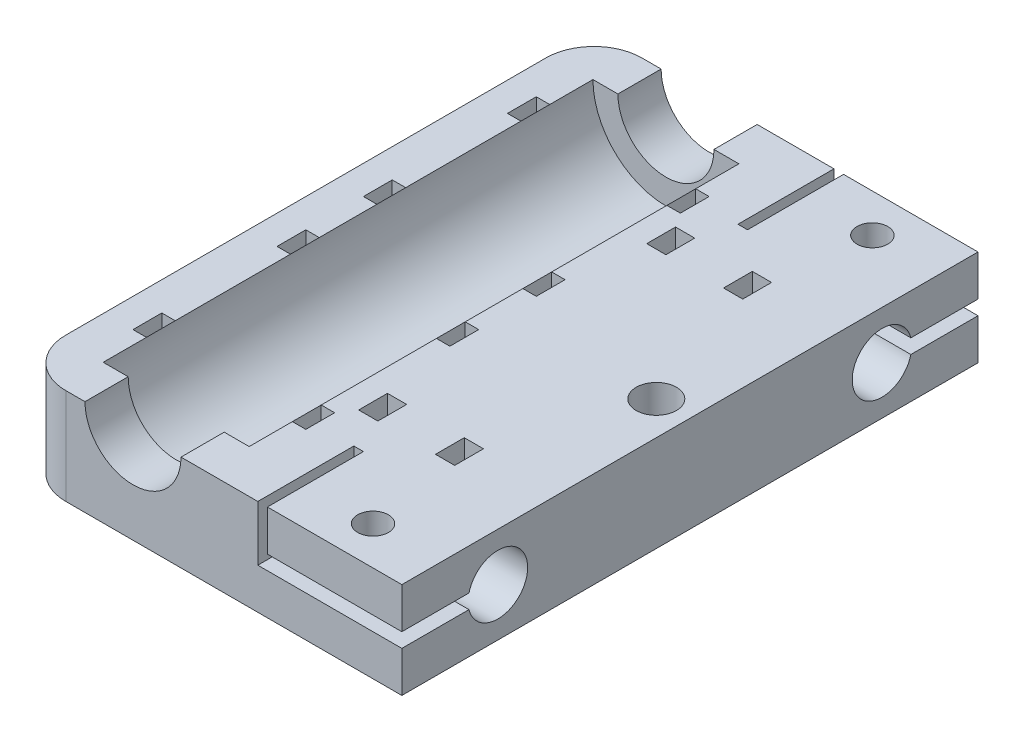
SolidWorks part; units mm, degrees
ref_plane "前基準面" through (0, 0, 0) normal (0, 0, 1) x (1, 0, 0)
ref_plane "上基準面" through (0, 0, 0) normal (0, 1, 0) x (1, 0, 0)
ref_plane "右基準面" through (0, 0, 0) normal (1, 0, 0) x (0, 0, -1)
sketch "草圖2" plane through (0, 0, 0) normal (0, 1, 0) x (1, 0, 0)
  line L1 (-20000, 30000) -> (20000, 30000)
  line L2 (-20000, 30000) -> (-20000, -30000)
  line L3 (-20000, -30000) -> (20000, -30000)
  line L4 (20000, 30000) -> (20000, -30000)
  line L5 (-20000, 30000) -> (20000, -30000) construction
  line L6 (-20000, -30000) -> (20000, 30000) construction
  point P0 (0, 0)
  dimension "D1" = 40000
  dimension "D2" = 60000
extrude "填料-伸長1" add sketch "草圖2" along normal blind 10000
sketch "草圖4" plane through (0, 0, 0) normal (0, 0, 1) x (1, 0, 0)
  line L0 (-20000, 10000) -> (20000, 10000) construction
  line L1 (-20000, 10000) -> (-20000, 0) construction
  circle A0 centre (-8000, 10000) radius 7600
  dimension "D1" = 15200
  dimension "D2" = 12000
extrude "除料-伸長2" cut sketch "草圖4" against normal mid plane 51000
sketch "草圖5" plane through (0, 0, 0) normal (0, 0, 1) x (1, 0, 0)
  circle A0 centre (-8000, 10000) radius 5000
  dimension "D1" = 10000
extrude "除料-伸長3" cut sketch "草圖5" against normal mid plane 80000
sketch "草圖6" plane through (0, 10000, 0) normal (0, 1, 0) x (1, 0, 0)
  line L0 (7000, 30000) -> (7000, -30000) construction
  line L1 (20000, 30000) -> (-3000, 30000) construction
  line L2 (-3000, -30000) -> (20000, -30000) construction
  line L3 (-13000, 25500) -> (-3000, 25500) construction
  line L4 (-20000, 0) -> (38738.6802, 0) construction
  line L5 (4000, 16500) -> (10000, 16500) construction
  line L6 (4000, 16500) -> (4000, 13500) construction
  line L7 (4000, 13500) -> (10000, 13500) construction
  line L8 (10000, 16500) -> (10000, 13500) construction
  line L9 (4000, 16500) -> (10000, 13500) construction
  line L10 (4000, 13500) -> (10000, 16500) construction
  line L11 (-20000, 30000) -> (-20000, -30000) construction
  line L12 (12000, -16500) -> (12000, -13500)
  line L13 (4000, 16500) -> (2000, 16500)
  line L14 (4000, 16500) -> (4000, 13500)
  line L15 (4000, 13500) -> (2000, 13500)
  line L16 (2000, 16500) -> (2000, 13500)
  line L17 (10000, 16500) -> (12000, 16500)
  line L18 (10000, 16500) -> (10000, 13500)
  line L19 (10000, 13500) -> (12000, 13500)
  line L20 (12000, 16500) -> (12000, 13500)
  line L21 (10000, -16500) -> (12000, -16500)
  line L22 (10000, -16500) -> (10000, -13500)
  line L23 (4000, -13500) -> (2000, -13500)
  line L24 (10000, -13500) -> (12000, -13500)
  line L25 (4000, -16500) -> (4000, -13500)
  line L26 (2000, -16500) -> (2000, -13500)
  line L27 (4000, -16500) -> (2000, -16500)
  point P8 (-8000, 25500)
  point P9 (7000, 15000)
  dimension "D1" = 15000
  dimension "D2" = 6000
  dimension "D3" = 3000
  dimension "D4" = 15000
  dimension "D5" = 2000
  dimension "D6" = 2000
extrude "除料-伸長4" cut sketch "草圖6" against normal blind 80000
sketch "草圖10" plane through (0, 10000, 0) normal (0, 1, 0) x (1, 0, 0)
  line L1 (-53500, -15500) -> (-53500, 15500) construction
  line L2 (-53500, -15500) -> (-22500, -15500) construction
  line L3 (-22500, -15500) -> (-22500, 15500) construction
  line L4 (-53500, 15500) -> (-22500, 15500) construction
  line L5 (-53500, -15500) -> (-22500, 15500) construction
  line L6 (-22500, -15500) -> (-53500, 15500) construction
  line L8 (-8000, 25500) -> (-8000, -13906.3177) construction
  line L9 (-13000, 25500) -> (-3000, 25500) construction
  point P0 (-38000, 0)
  dimension "D1" = 31000
  dimension "D2" = 31000
  dimension "D3" = 30000
sketch "草圖12" plane through (0, 10000, 0) normal (0, 1, 0) x (1, 0, 0)
  line L0 (-53500, -15500) -> (-22500, 15500) construction
  line L1 (-20000, 30000) -> (-58000, 30000)
  line L2 (-20000, 30000) -> (-20000, -30000)
  line L3 (-20000, -30000) -> (-58000, -30000)
  line L4 (-58000, 30000) -> (-58000, -30000)
  line L5 (-20000, -30000) -> (-13000, -30000) construction
  circle A0 centre (-53500, 15500) radius 1600
  circle A1 centre (-22500, 15500) radius 1600
  circle A2 centre (-53500, -15500) radius 1600
  circle A3 centre (-22500, -15500) radius 1600
  circle A4 centre (-38000, 0) radius 11250
  dimension "D2" = 3200
  dimension "D3" = 3200
  dimension "D4" = 3200
  dimension "D5" = 3200
  dimension "D6" = 22500
  dimension "D1" = 38000
sketch "草圖13" plane through (20000, 0, 0) normal (1, 0, 0) x (0, 0, -1)
  line L0 (0, 11922.9918) -> (0, -4401.0139) construction
  circle A0 centre (-20000, 5000) radius 3100
  circle A1 centre (20000, 5000) radius 3100
  dimension "D1" = 6200
  dimension "D2" = 20000
extrude "除料-伸長6" cut sketch "草圖13" against normal blind 18000
sketch "草圖15" plane through (0, 10000, 0) normal (0, 1, 0) x (1, 0, 0)
  line L0 (-22500, -15500) -> (-53500, 15500) construction
  line L1 (-59000, -21000) -> (-17000, -21000) construction
  line L2 (-59000, -21000) -> (-59000, 21000) construction
  line L3 (-59000, 21000) -> (-17000, 21000) construction
  line L4 (-17000, -21000) -> (-17000, 21000) construction
  line L5 (-59000, -21000) -> (-17000, 21000) construction
  line L6 (-59000, 21000) -> (-17000, -21000) construction
  point P0 (-38000, 0)
  dimension "D1" = 42000
  dimension "D2" = 42000
sketch "草圖16" plane through (20000, 0, 0) normal (1, 0, 0) x (0, 0, -1)
  line L0 (0, 10000) -> (0, -6413.2276) construction
  line L1 (-20000, 5000) -> (-32080.4356, 5000) construction
  line L2 (31055.9576, 4250) -> (21024.478, 5750) construction
  line L3 (-31055.9576, 5750) -> (-21024.478, 5750)
  line L4 (-31055.9576, 5750) -> (-31055.9576, 4250)
  line L5 (-31055.9576, 4250) -> (-21024.478, 4250)
  line L6 (-21024.478, 5750) -> (-21024.478, 4250)
  line L7 (-31055.9576, 5750) -> (-21024.478, 4250) construction
  line L8 (-31055.9576, 4250) -> (-21024.478, 5750) construction
  line L9 (31055.9576, 5750) -> (21024.478, 4250) construction
  line L10 (20000, 5000) -> (32080.4356, 5000) construction
  line L11 (21024.478, 5750) -> (21024.478, 4250)
  line L12 (31055.9576, 4250) -> (21024.478, 4250)
  line L13 (31055.9576, 5750) -> (31055.9576, 4250)
  line L14 (31055.9576, 5750) -> (21024.478, 5750)
  point P2 (-26040.2178, 5000)
  point P18 (26040.2178, 5000)
  dimension "D1" = 10031.4796
  dimension "D2" = 1500
extrude "除料-伸長7" cut sketch "草圖16" against normal blind 15000
sketch "草圖17" plane through (0, 10000, 0) normal (0, 1, 0) x (1, 0, 0)
  line L0 (20320.3387, 0) -> (-9687.0538, 0) construction
  line L1 (5000, 30000) -> (6000, 30000)
  line L2 (5000, 30000) -> (5000, 20000)
  line L3 (5000, 20000) -> (6000, 20000)
  line L4 (6000, 30000) -> (6000, 20000)
  line L5 (6000, -30000) -> (6000, -20000)
  line L6 (5000, -20000) -> (6000, -20000)
  line L7 (5000, -30000) -> (5000, -20000)
  line L8 (5000, -30000) -> (6000, -30000)
  dimension "D1" = 1000
  dimension "D2" = 10000
extrude "除料-伸長8" cut sketch "草圖17" against normal up to surface (5750 mm away) up to face at (12500, 4250, -26503.9531)
sketch "草圖18" plane through (0, 10000, 0) normal (0, 1, 0) x (1, 0, 0)
  line L0 (0, 0) -> (36287.083, 0) construction
  line L1 (20000, 30000) -> (6000, 30000) construction
  circle A0 centre (13000, 26000) radius 1600
  circle A1 centre (13000, -26000) radius 1600
  dimension "D1" = 3200
  dimension "D2" = 4000
extrude "除料-伸長9" cut sketch "草圖18" against normal blind 15000
sketch "草圖19" plane through (0, 10000, 0) normal (0, 1, 0) x (1, 0, 0)
  line L0 (-15600, 0) -> (22136.2106, 0) construction
  line L1 (-15600, 25500) -> (-15600, -25500) construction
  line L2 (-15600, 12000) -> (5685.0909, 12000) construction
  line L3 (-15600, -12000) -> (2799.4169, -12000) construction
  line L4 (-17000, -21000) -> (-17000, 21000) construction
  line L5 (-15600, 21000) -> (-17000, 21000)
  line L6 (-15600, 21000) -> (-15600, 18000)
  line L7 (-15600, 18000) -> (-17000, 18000)
  line L8 (-17000, 21000) -> (-17000, 18000)
  line L9 (-59000, 21000) -> (-17000, 21000) construction
  line L10 (-15600, 3000) -> (-15600, 6000)
  line L11 (-15600, 6000) -> (-17000, 6000)
  line L12 (-17000, 3000) -> (-17000, 6000)
  line L13 (-15600, 3000) -> (-17000, 3000)
  line L14 (-15600, -3000) -> (-17000, -3000)
  line L15 (-17000, -3000) -> (-17000, -6000)
  line L16 (-15600, -6000) -> (-17000, -6000)
  line L17 (-15600, -3000) -> (-15600, -6000)
  line L18 (-17000, -21000) -> (-17000, -18000)
  line L19 (-15600, -18000) -> (-17000, -18000)
  line L20 (-15600, -21000) -> (-15600, -18000)
  line L21 (-15600, -21000) -> (-17000, -21000)
  line L22 (-8000, 25500) -> (-8000, -25500) construction
  line L23 (-13000, 25500) -> (-3000, 25500) construction
  line L24 (-400, -25500) -> (-15600, -25500) construction
  line L25 (-400, -21000) -> (1000, -21000)
  line L26 (-400, -21000) -> (-400, -18000)
  line L27 (-400, -18000) -> (1000, -18000)
  line L28 (1000, -21000) -> (1000, -18000)
  line L29 (-400, -3000) -> (-400, -6000)
  line L30 (-400, -6000) -> (1000, -6000)
  line L31 (1000, -3000) -> (1000, -6000)
  line L32 (-400, -3000) -> (1000, -3000)
  line L33 (-400, 3000) -> (1000, 3000)
  line L34 (1000, 3000) -> (1000, 6000)
  line L35 (-400, 6000) -> (1000, 6000)
  line L36 (-400, 3000) -> (-400, 6000)
  line L37 (1000, 21000) -> (1000, 18000)
  line L38 (-400, 18000) -> (1000, 18000)
  line L39 (-400, 21000) -> (-400, 18000)
  line L40 (-400, 21000) -> (1000, 21000)
  point P17 (-15600, 19500)
  point P18 (-15600, 4500)
  point P27 (-15600, -4500)
  point P54 (-400, -4500)
  point P55 (-400, 4500)
  dimension "D1" = 12000
  dimension "D2" = 12000
  dimension "D3" = 3000
extrude "除料-伸長10" cut sketch "草圖19" against normal blind 15000
fillet "圓角1" radius 5000 2 edges at (-20000, 5000, -30000) (-20000, 5000, 30000)
sketch "草圖20" plane through (0, 10000, 0) normal (0, 1, 0) x (1, 0, 0)
  line L1 (10000, 13500) -> (10000, -13500) construction
  circle A0 centre (16500, 0) radius 2100
  circle A1 centre (16500, 0) radius 6500 construction
  dimension "D1" = 4200
  dimension "D3" = 13000
extrude "除料-伸長11" cut sketch "草圖20" against normal blind 10000
sketch "草圖21" plane through (0, 0, 0) normal (0, -1, 0) x (1, 0, 0)
  line L1 (4000, 16500) -> (10000, 16500)
  line L2 (4000, 16500) -> (4000, 13500)
  line L3 (4000, 13500) -> (10000, 13500)
  line L4 (10000, 16500) -> (10000, 13500)
  line L5 (4000, -13500) -> (10000, -13500)
  line L6 (4000, -13500) -> (4000, -16500)
  line L7 (4000, -16500) -> (10000, -16500)
  line L8 (10000, -13500) -> (10000, -16500)
extrude "除料-伸長12" cut sketch "草圖21" against normal blind 2000
fillet "圓角2" radius 1000 4 edges at (10000, 2000, -15000) (4000, 2000, -15000) (10000, 2000, 15000) (4000, 2000, 15000)
